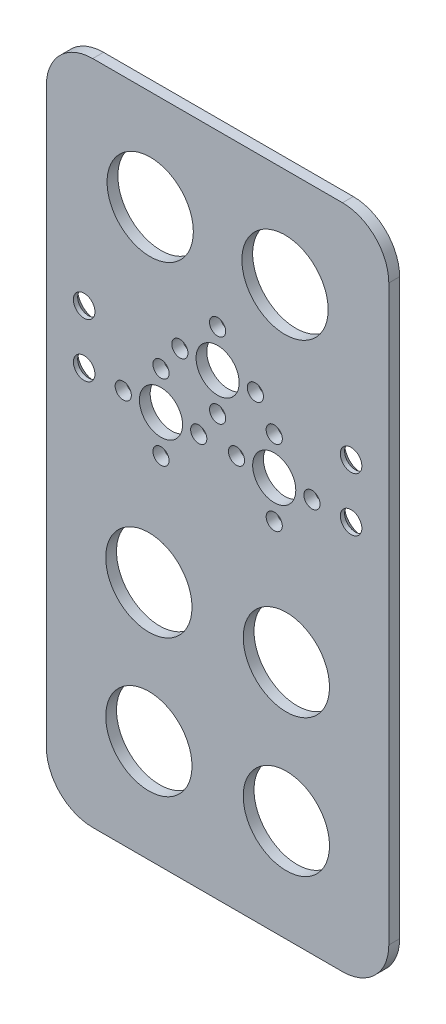
SolidWorks part; units mm, degrees
ref_plane "前视" through (0, 0, 0) normal (0, 0, 1) x (1, 0, 0)
ref_plane "上视" through (0, 0, 0) normal (0, 1, 0) x (1, 0, 0)
ref_plane "右视" through (0, 0, 0) normal (1, 0, 0) x (0, 0, -1)
sketch "草图1" plane through (0, 0, 0) normal (0, 0, 1) x (1, 0, 0)
  line L0 (-23.1621, -54.533) -> (23.1621, -54.533)
  line L1 (0, 75.1709) -> (0, 24.4519) construction
  line L2 (-31.75, -45.9451) -> (-31.75, 60.379)
  line L3 (-23.1621, 68.967) -> (23.1621, 68.967)
  line L4 (31.75, -45.9451) -> (31.75, 60.379)
  line L5 (0, 50.467) -> (-12.5, 50.467) construction
  line L6 (0, 50.467) -> (12.5, 50.467) construction
  line L8 (0, 18.467) -> (-24.75, 18.467) construction
  line L9 (0, 18.467) -> (24.75, 18.467) construction
  line L10 (-24.75, 18.467) -> (-24.75, 28.467) construction
  line L11 (24.75, 18.467) -> (24.75, 22.6139) construction
  line L12 (0, -54.533) -> (0, -35.4269) construction
  line L13 (12.75, -35.533) -> (12.75, -10.033) construction
  arc A0 (-31.75, -45.9451) -> (-23.1621, -54.533) centre (-23.1621, -45.9451) ccw
  arc A1 (23.1621, -54.533) -> (31.75, -45.9451) centre (23.1621, -45.9451) ccw
  arc A2 (31.75, 60.379) -> (23.1621, 68.967) centre (23.1621, 60.379) ccw
  arc A3 (-31.75, 60.379) -> (-23.1621, 68.967) centre (-23.1621, 60.379) cw
  circle A4 centre (-12.5, 50.467) radius 8
  circle A5 centre (12.5, 50.467) radius 8
  circle A6 centre (-12.7499, -35.4633) radius 8
  circle A7 centre (12.75, -35.533) radius 8
  circle A8 centre (12.75, -10.033) radius 8
  circle A9 centre (-12.7499, -9.9633) radius 8
  circle A10 centre (24.75, 28.467) radius 2
  circle A11 centre (24.75, 18.467) radius 2
  circle A12 centre (-24.75, 28.467) radius 2
  circle A13 centre (-24.75, 18.467) radius 2
  circle A14 centre (0, 30.467) radius 4
  circle A15 centre (-10.5, 18.467) radius 4
  circle A16 centre (10.5, 18.467) radius 4
  circle A17 centre (10.5, 25.467) radius 1.5
  circle A18 centre (0, 37.467) radius 1.5
  circle A19 centre (7, 30.467) radius 1.5
  circle A20 centre (-10.5, 25.467) radius 1.5
  circle A21 centre (0, 23.467) radius 1.5
  circle A22 centre (-7, 30.467) radius 1.5
  circle A23 centre (17.5, 18.467) radius 1.5
  circle A24 centre (10.5, 11.467) radius 1.5
  circle A25 centre (3.5, 18.467) radius 1.5
  circle A26 centre (-3.5, 18.467) radius 1.5
  circle A27 centre (-10.5, 11.467) radius 1.5
  circle A28 centre (-17.5, 18.467) radius 1.5
  point P7 (0, 0)
  point P41 (24.75, 28.467)
  point P42 (24.75, 18.467)
  point P43 (-24.75, 28.467)
  point P44 (-24.75, 18.467)
  point P61 (-1.3482, 0)
  point P67 (0, 30.467)
  point P74 (10.5, 18.467)
  point P81 (-10.5, 18.467)
  dimension "D1" = 8
  dimension "D2" = 8
  dimension "D3" = 8
  dimension "D6" = 3
  dimension "D11" = 16
  dimension "D12" = 16
  dimension "D17" = 4
  dimension "D18" = 4
  dimension "D19" = 4
  dimension "D20" = 4
  dimension "D24" = 3
  dimension "D26" = 3
  dimension "D31" = 16
  dimension "D32" = 16
  dimension "D33" = 16
  dimension "D34" = 16
  dimension "D4" = 7
  dimension "D5" = 7
  dimension "D7" = 7
  dimension "D9" = 63.5
  dimension "D10" = 123.5
  dimension "D13" = 12.5
  dimension "D14" = 12.5
  dimension "D15" = 18.5
  dimension "D16" = 20
  dimension "D21" = 10
  dimension "D22" = 10
  dimension "D23" = 12
  dimension "D8" = 21
  dimension "D25" = 7
  dimension "D27" = 7
  dimension "D28" = 25.5
  dimension "D29" = 25.5
  dimension "D30" = 25.5
  dimension "D35" = 12.75
  dimension "D36" = 19
  dimension "D37" = 68.967
extrude "凸台-拉伸1" add sketch "草图1" along normal blind 2
hole_wizard "打孔尺寸开槽半沉头螺钉的类型1" positions "3D草图3" profile "草图4" countersink size "M3" standard "GB"
sketch3d "3D草图3"
  line L0 (24.75, 28.467, 2) -> (24.75, 28.467, 0) construction
  line L1 (24.75, 18.467, 2) -> (24.75, 18.467, 0) construction
  line L2 (-24.75, 18.467, 2) -> (-24.75, 18.467, 0) construction
  line L3 (-24.75, 28.467, 2) -> (-24.75, 28.467, 0) construction
  point P0 (24.75, 28.467, 0)
  point P4 (24.75, 18.467, 0)
  point P8 (-24.75, 18.467, 0)
  point P12 (-24.75, 28.467, 0)
sketch "草图4" plane through (24.75, 28.467, 0) normal (1, 0, 0) x (0, 1, 0)
  line L0 (0, 0) -> (0, 3.0215)
  line L1 (0, 3.0215) -> (1.7, 2)
  line L2 (1.7, 2) -> (1.7, 1.5)
  line L3 (1.7, 1.5) -> (3.2, 0)
  line L5 (3.2, 0) -> (0, 0)
  line L6 (-1.7, 1.5) -> (-3.2, 0) construction
  line L10 (0, 3.0215) -> (-1.7, 2) construction
  line L11 (0, -6.35) -> (0, 107.95) construction
  dimension "孔直径" = 3.4
  dimension "孔深度" = 2
  dimension "近端锥形沉头孔直径" = 6.4
  dimension "近端锥形沉头孔角度" = 90
  dimension "导头角度" = 118
